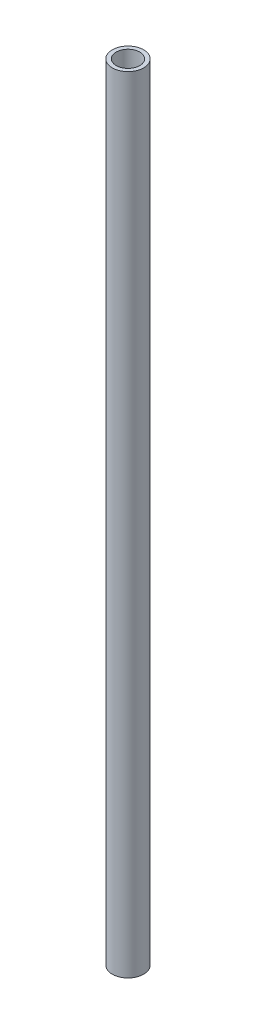
SolidWorks part; units mm, degrees
ref_plane "Front Plane" through (0, 0, 0) normal (0, 0, 1) x (1, 0, 0)
ref_plane "Top Plane" through (0, 0, 0) normal (0, 1, 0) x (1, 0, 0)
ref_plane "Right Plane" through (0, 0, 0) normal (1, 0, 0) x (0, 0, -1)
sketch "Sketch1" plane through (0, 0, 0) normal (0, 1, 0) x (1, 0, 0)
  circle A0 centre (0, 0) radius 3
  circle A1 centre (0, 0) radius 4
  dimension "D1" = 6
  dimension "D2" = 8
extrude "Boss-Extrude1" add sketch "Sketch1" along normal mid plane 200
